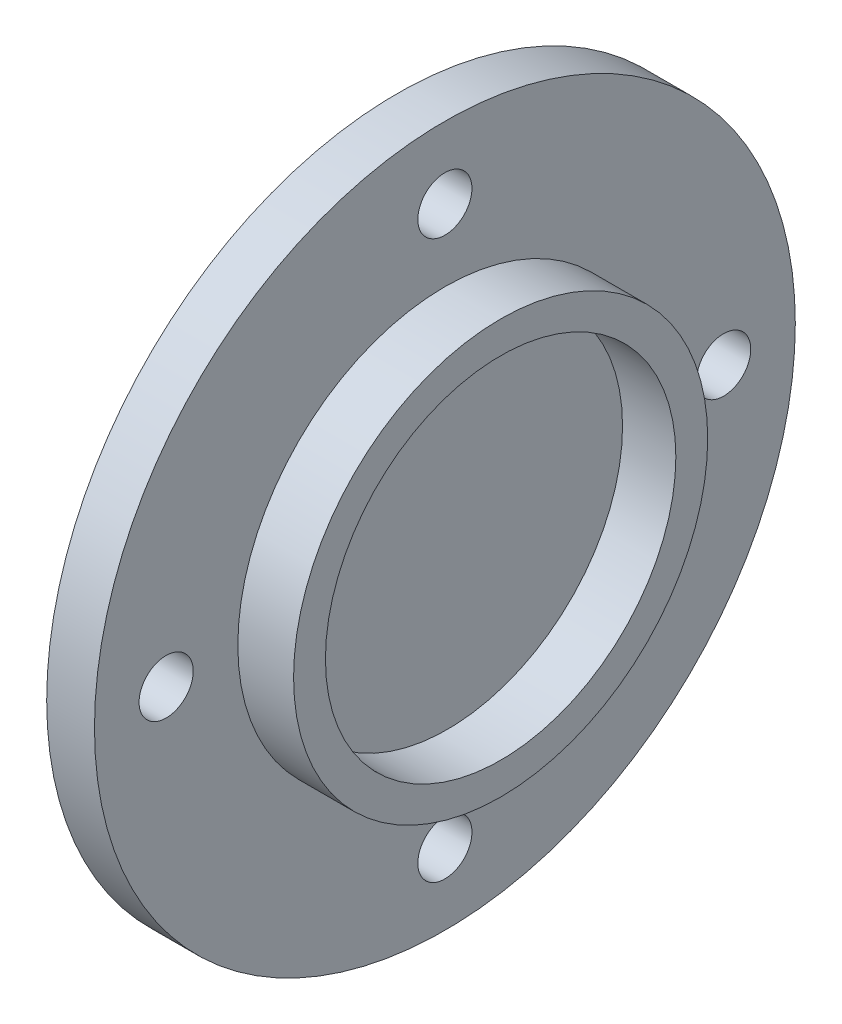
SolidWorks part; units mm, degrees
ref_plane "Front Plane" through (0, 0, 0) normal (0, 0, 1) x (1, 0, 0)
ref_plane "Top Plane" through (0, 0, 0) normal (0, 1, 0) x (1, 0, 0)
ref_plane "Right Plane" through (0, 0, 0) normal (1, 0, 0) x (0, 0, -1)
sketch "Sketch1" plane through (0, 0, 0) normal (0, 0, 1) x (1, 0, 0)
  line L0 (-37.1538, 0) -> (43.9615, 0) construction
  line L1 (-13, 0) -> (-13, 44)
  line L2 (-13, 44) -> (-7, 44)
  line L3 (-7, 44) -> (-7, 26)
  line L4 (-7, 26) -> (0, 26)
  line L5 (0, 26) -> (0, 22)
  line L6 (0, 22) -> (-6.6923, 22)
  line L7 (-6.6923, 22) -> (-6.6923, 0)
  line L9 (-13, 0) -> (-6.6923, 0)
  dimension "D1" = 6
  dimension "D2" = 13
  dimension "D3" = 88
  dimension "D4" = 44
  dimension "D5" = 52
revolve "Revolve1" add sketch "Sketch1" angle 360 about L0
sketch "Sketch2" plane through (-13, 0, 0) normal (-1, 0, 0) x (0, 0, 1)
  circle A0 centre (0, 0) radius 35 construction
  point P3 (-82.2214, 32.5355)
  point P4 (0, 35)
  point P5 (-35, 0)
  point P6 (0, -35)
  point P7 (35, 0)
hole_wizard "M8 Tapped Hole1" positions "3DSketch1" profile "Sketch3" tap size "M8" standard "ISO"
sketch3d "3DSketch1"
  point P0 (-13, 0, -35)
  point P3 (-13, -35, 0)
  point P6 (-13, 0, 35)
  point P9 (-13, 35, 0)
sketch "Sketch3" plane through (-13, 0, -35) normal (0, 1, 0) x (0, 0, 1)
  line L0 (0, 0) -> (0, 18.0429)
  line L1 (0, 18.0429) -> (3.4, 16)
  line L2 (3.4, 16) -> (3.4, 0)
  line L5 (3.4, 0) -> (0, 0)
  line L10 (0, 18.0429) -> (-3.4, 16) construction
  line L11 (0, -6.35) -> (0, 107.95) construction
  dimension "Tap Drill Dia." = 6.8
  dimension "Tap Drill Depth" = 16
  dimension "Drill Angle" = 118
cosmetic thread "Hole Thread1" parameters "D1"=16, "D2"=8
cosmetic thread "Hole Thread2" parameters "D1"=16, "D2"=8
cosmetic thread "Hole Thread3" parameters "D1"=16, "D2"=8
cosmetic thread "Hole Thread4" parameters "D1"=16, "D2"=8
